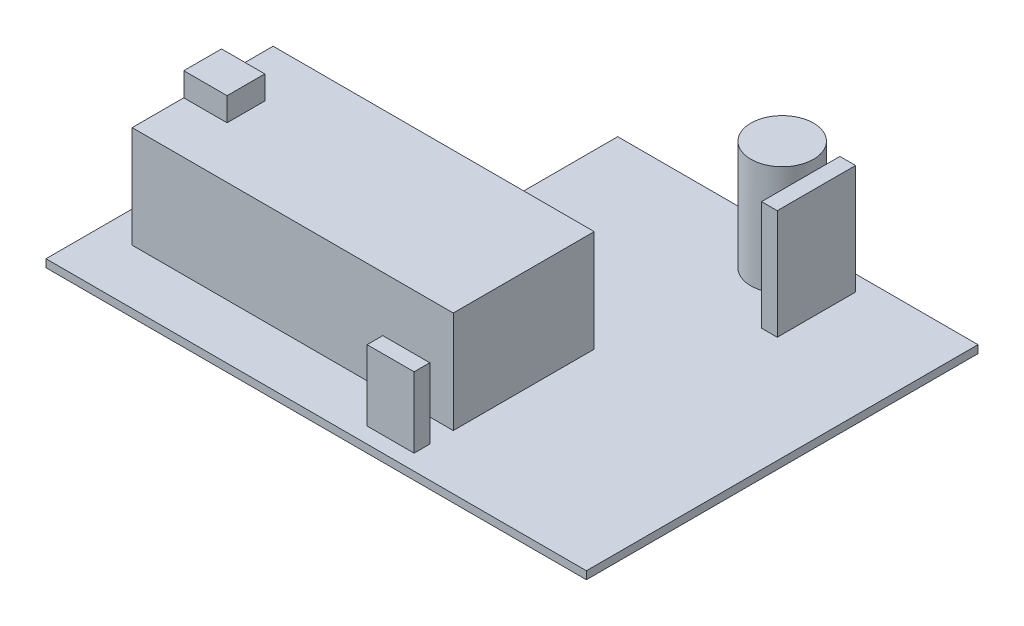
SolidWorks part; units mm, degrees
ref_plane "Front Plane" through (0, 0, 0) normal (0, 0, 1) x (1, 0, 0)
ref_plane "Top Plane" through (0, 0, 0) normal (0, 1, 0) x (1, 0, 0)
ref_plane "Right Plane" through (0, 0, 0) normal (1, 0, 0) x (0, 0, -1)
sketch "Sketch2" plane through (0, 0, 0) normal (0, 1, 0) x (1, 0, 0)
  line L1 (0, 0) -> (69, 0)
  line L2 (0, 0) -> (0, 50)
  line L3 (0, 50) -> (69, 50)
  line L4 (69, 0) -> (69, 50)
  line L5 (0, 50) -> (23, 50)
  line L6 (0, 50) -> (0, 32)
  line L7 (0, 32) -> (23, 32)
  line L8 (23, 50) -> (23, 32)
  dimension "D1" = 69
  dimension "D2" = 50
  dimension "D3" = 23
  dimension "D4" = 18
extrude "Boss-Extrude1" add sketch "Sketch2" along normal blind 1 contours L3 L8 L7 L2 L1 L4
sketch "Sketch3" plane through (0, 1, 0) normal (0, 1, 0) x (1, 0, 0)
  line L0 (0, 0) -> (69, 0) construction
  line L1 (4, 25) -> (45, 25)
  line L2 (4, 25) -> (4, 7)
  line L3 (4, 7) -> (45, 7)
  line L4 (45, 25) -> (45, 7)
  line L5 (0, 0) -> (0, 32) construction
  dimension "D1" = 41
  dimension "D2" = 18
  dimension "D3" = 7
  dimension "D4" = 4
extrude "Boss-Extrude2" add sketch "Sketch3" along normal blind 13
sketch "Sketch4" plane through (0, 14, 0) normal (0, 1, 0) x (1, 0, 0)
  line L0 (4, 25) -> (4, 7) construction
  line L1 (4, 18.4086) -> (9.528, 18.4086)
  line L2 (4, 18.4086) -> (4, 13.5914)
  line L3 (4, 13.5914) -> (9.528, 13.5914)
  line L4 (9.528, 18.4086) -> (9.528, 13.5914)
  line L5 (45, 7) -> (45, 25) construction
  point P6 (9.528, 16)
  point P7 (45, 16)
  point P8 (0, 0)
extrude "Boss-Extrude3" add sketch "Sketch4" along normal blind 3
sketch "Sketch5" plane through (0, 1, 0) normal (0, 1, 0) x (1, 0, 0)
  line L0 (45, 7) -> (45, 25) construction
  line L1 (45, 4) -> (39, 4)
  line L2 (45, 4) -> (45, 2)
  line L3 (45, 2) -> (39, 2)
  line L4 (39, 4) -> (39, 2)
  line L5 (0, 0) -> (69, 0) construction
  dimension "D1" = 6
  dimension "D2" = 2
  dimension "D3" = 2
extrude "Boss-Extrude4" add sketch "Sketch5" along normal blind 9
sketch "Sketch6" plane through (0, 1, 0) normal (0, 1, 0) x (1, 0, 0)
  line L0 (69, 0) -> (69, 50) construction
  line L1 (23, 50) -> (69, 50) construction
  circle A0 centre (48, 46) radius 4
  dimension "D1" = 8
  dimension "D2" = 21
extrude "Boss-Extrude5" add sketch "Sketch6" along normal blind 14
sketch "Sketch7" plane through (0, 1, 0) normal (0, 1, 0) x (1, 0, 0)
  line L0 (48, 50) -> (69, 50) construction
  line L1 (53.3685, 48) -> (55.3685, 48)
  line L2 (53.3685, 48) -> (53.3685, 38)
  line L3 (53.3685, 38) -> (55.3685, 38)
  line L4 (55.3685, 48) -> (55.3685, 38)
  dimension "D1" = 2
  dimension "D2" = 10
  dimension "D3" = 2
extrude "Boss-Extrude6" add sketch "Sketch7" along normal blind 14
